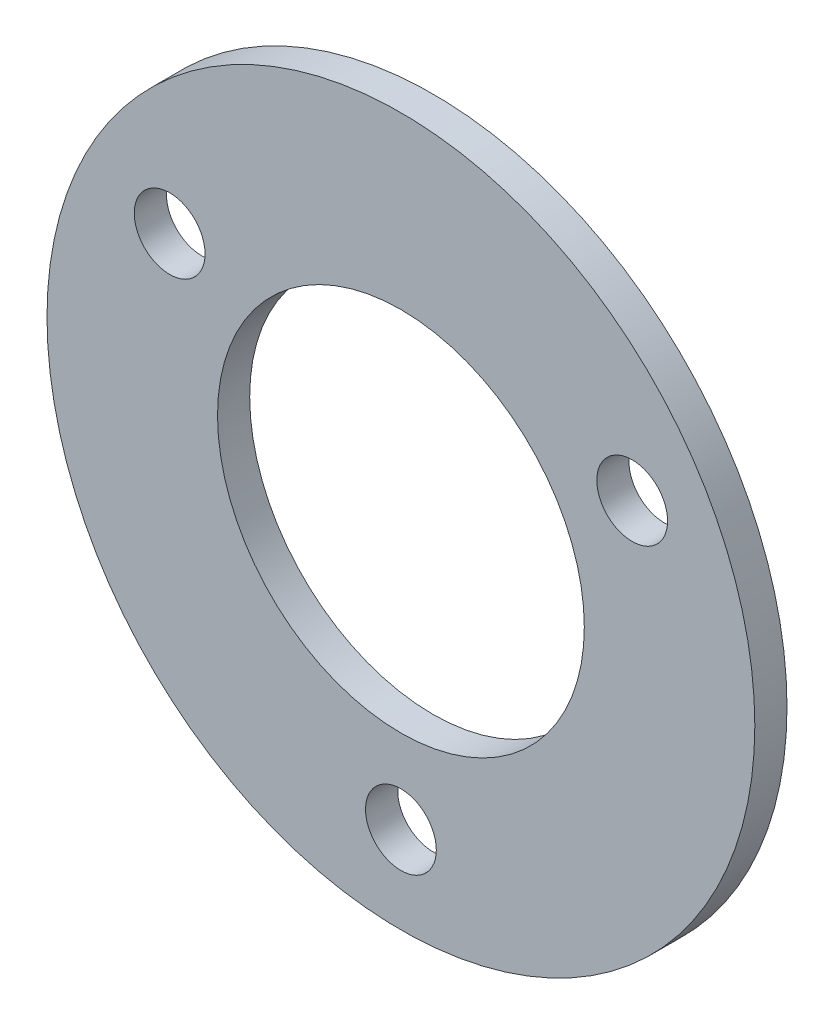
SolidWorks part; units mm, degrees
ref_plane "Front Plane" through (0, 0, 0) normal (0, 0, 1) x (1, 0, 0)
ref_plane "Top Plane" through (0, 0, 0) normal (0, 1, 0) x (1, 0, 0)
ref_plane "Right Plane" through (0, 0, 0) normal (1, 0, 0) x (0, 0, -1)
sketch "Sketch1" plane through (0, 0, 0) normal (0, 0, 1) x (1, 0, 0)
  circle A0 centre (0, 0) radius 11
  circle A1 centre (0, 0) radius 5.7
  circle A2 centre (7.188, 4.15) radius 1.1
  circle A3 centre (-7.188, 4.15) radius 1.1
  circle A4 centre (0, -8.3) radius 1.1
extrude "Bearing_Cap" add sketch "Sketch1" along normal blind 1
